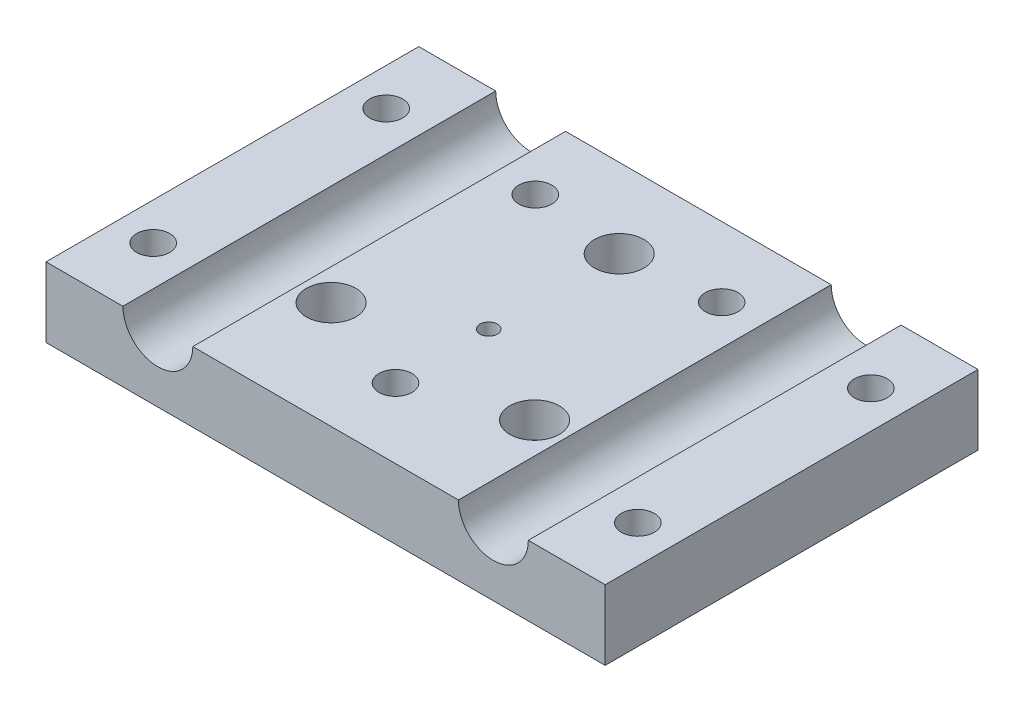
SolidWorks part; units mm, degrees
material "Copper"
ref_plane "Front Plane" through (0, 0, 0) normal (0, 0, 1) x (1, 0, 0)
ref_plane "Top Plane" through (0, 0, 0) normal (0, 1, 0) x (1, 0, 0)
ref_plane "Right Plane" through (0, 0, 0) normal (1, 0, 0) x (0, 0, -1)
sketch "Sketch1" plane through (0, 0, 0) normal (0, 1, 0) x (1, 0, 0)
  line L1 (-38.1, 25.4) -> (38.1, 25.4)
  line L2 (-38.1, 25.4) -> (-38.1, -25.4)
  line L3 (-38.1, -25.4) -> (38.1, -25.4)
  line L4 (38.1, 25.4) -> (38.1, -25.4)
  dimension "D1" = 50.8
  dimension "D2" = 76.2
  dimension "D3" = 38.1
  dimension "D4" = 25.4
extrude "Boss-Extrude1" add sketch "Sketch1" along normal blind 9.525
hole_wizard "1/4 Clearance Hole1" positions "Sketch3" profile "Sketch2" hole size "1/4" standard "ANSI Inch" end condition through all
sketch "Sketch3" plane through (0, 9.525, 0) normal (0, 1, 0) x (1, 0, 0)
  point P0 (0, 14.6101)
  point P2 (-13.8608, -10.7899)
  point P4 (13.8608, -10.7899)
  dimension "D1" = 10.7899
  dimension "D2" = 14.6101
  dimension "D3" = 13.8608
  dimension "D4" = 27.7216
sketch "Sketch2" plane through (0, 9.525, -14.6101) normal (1, 0, 0) x (0, 0, 1)
  line L0 (0, 0) -> (0, 9.525)
  line L1 (0, 9.525) -> (3.3782, 9.525)
  line L2 (3.3782, 9.525) -> (3.3782, 0)
  line L5 (3.3782, 0) -> (0, 0)
  line L11 (0, -6.35) -> (0, 107.95) construction
  dimension "Thru Hole Dia." = 6.7564
  dimension "Thru Hole Depth" = 9.525
sketch "Sketch4" plane through (0, 0, 25.4) normal (0, 0, 1) x (1, 0, 0)
  line L0 (-38.1, 9.525) -> (38.1, 9.525) construction
  line L1 (-27.6225, 9.525) -> (-18.0975, 9.525)
  line L2 (18.0975, 9.525) -> (27.6225, 9.525)
  arc A0 (-27.6225, 9.525) -> (-18.0975, 9.525) centre (-22.86, 9.525) ccw
  arc A1 (18.0975, 9.525) -> (27.6225, 9.525) centre (22.86, 9.525) ccw
  dimension "D1" = 4.7625
  dimension "D2" = 4.7625
  dimension "D3" = 22.86
  dimension "D4" = 22.86
extrude "Cut-Extrude1" cut sketch "Sketch4" against normal through all
sketch "Sketch5" plane through (0, 9.525, 0) normal (0, 1, 0) x (1, 0, 0)
  circle A0 centre (0, -3.175) radius 1.1906
  dimension "D1" = 3.175
  dimension "D2" = 2.3813
extrude "Cut-Extrude2" cut sketch "Sketch5" against normal through all
hole_wizard "#8 Clearance Hole1" positions "Sketch7" profile "Sketch6" hole size "#8" standard "ANSI Inch" end condition through all
sketch "Sketch7" plane through (0, 9.525, 0) normal (0, 1, 0) x (1, 0, 0)
  point P0 (-33.02, 15.875)
  point P2 (-33.02, -15.875)
  point P4 (33.02, -15.875)
  point P6 (33.02, 15.875)
  point P14 (-12.7, 15.875)
  point P16 (12.7, 15.875)
  point P18 (0, -15.875)
  dimension "D1" = 33.02
  dimension "D2" = 15.875
  dimension "D3" = 15.875
  dimension "D4" = 33.02
  dimension "D5" = 12.7
  dimension "D6" = 12.7
sketch "Sketch6" plane through (-33.02, 9.525, -15.875) normal (1, 0, 0) x (0, 0, 1)
  line L0 (0, 0) -> (0, 9.525)
  line L1 (0, 9.525) -> (2.2479, 9.525)
  line L2 (2.2479, 9.525) -> (2.2479, 0)
  line L5 (2.2479, 0) -> (0, 0)
  line L11 (0, -6.35) -> (0, 107.95) construction
  dimension "Thru Hole Dia." = 4.4958
  dimension "Thru Hole Depth" = 9.525
sketch "Sketch8" plane through (0, 0, 0) normal (0, -1, 0) x (1, 0, 0)
  circle A3 centre (-13.8608, 10.7899) radius 5.08
  circle A4 centre (13.8608, 10.7899) radius 5.08
  circle A5 centre (0, -14.6101) radius 5.08
  dimension "D1" = 10.16
extrude "Cut-Extrude3" cut sketch "Sketch8" against normal blind 4.7625
sketch "Sketch9" plane through (0, 0, 0) normal (0, -1, 0) x (1, 0, 0)
  circle A7 centre (-33.02, 15.875) radius 3.81
  circle A8 centre (0, 15.875) radius 3.81
  circle A9 centre (33.02, 15.875) radius 3.81
  circle A10 centre (33.02, -15.875) radius 3.81
  circle A11 centre (12.7, -15.875) radius 3.81
  circle A12 centre (-12.7, -15.875) radius 3.81
  circle A13 centre (-33.02, -15.875) radius 3.81
  dimension "D1" = 7.62
extrude "Cut-Extrude4" cut sketch "Sketch9" against normal blind 4.7625
